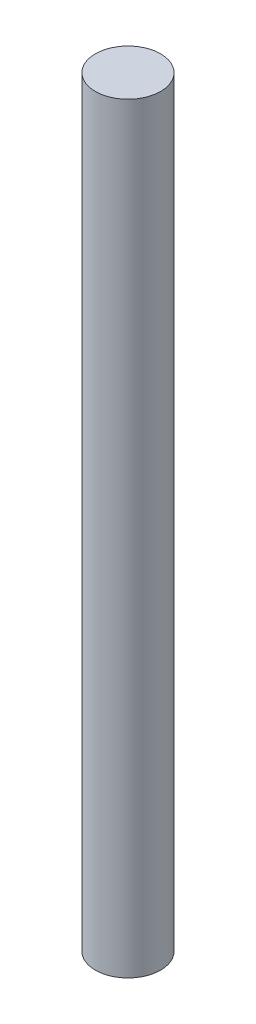
SolidWorks part; units mm, degrees
ref_plane "Plan de face" through (0, 0, 0) normal (0, 0, 1) x (1, 0, 0)
ref_plane "Plan de dessus" through (0, 0, 0) normal (0, 1, 0) x (1, 0, 0)
ref_plane "Plan de droite" through (0, 0, 0) normal (1, 0, 0) x (0, 0, -1)
sketch "Sketch1" plane through (0, 0, 0) normal (0, 1, 0) x (1, 0, 0)
  circle A0 centre (0, 0) radius 1.5
extrude "Boss-Extrude1" add sketch "Sketch1" along normal blind 35
